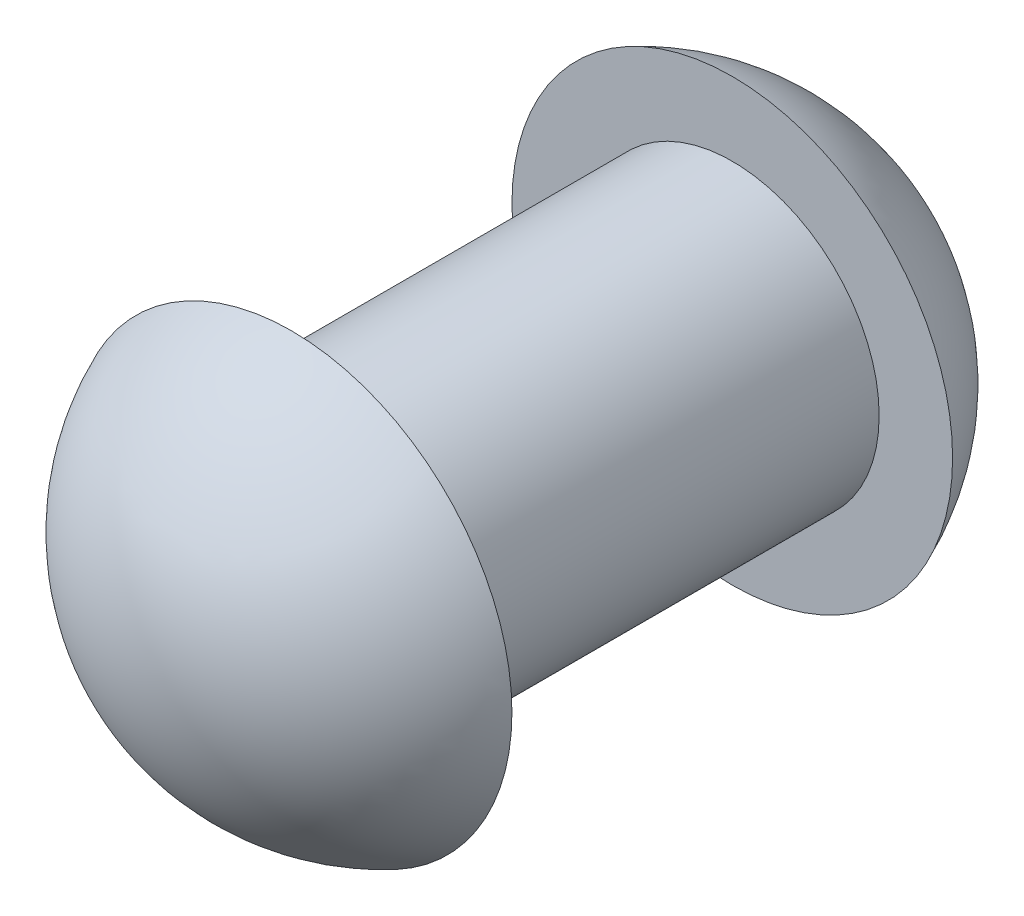
SolidWorks part; units mm, degrees
ref_plane "前视基准面" through (0, 0, 0) normal (0, 0, 1) x (1, 0, 0)
ref_plane "上视基准面" through (0, 0, 0) normal (0, 1, 0) x (1, 0, 0)
ref_plane "右视基准面" through (0, 0, 0) normal (1, 0, 0) x (0, 0, -1)
sketch "草图1" plane through (0, 0, 0) normal (0, 1, 0) x (1, 0, 0)
  line L0 (0, 2.5) -> (0, -2.5)
  line L1 (1.5, 1.5) -> (1, 1.5)
  line L2 (1, 1.5) -> (1, -1.5)
  line L3 (1, -1.5) -> (1.5, -1.5)
  arc A0 (0, 2.5) -> (1.5, 1.5) centre (0, 0.875) cw
  arc A1 (1.5, -1.5) -> (0, -2.5) centre (0, -0.875) cw
  point P3 (0, 0)
  point P10 (1, 0)
  point P11 (0.1939, -0.792)
  dimension "D1" = 0.5
  dimension "D2" = 1
  dimension "D3" = 3
  dimension "D4" = 5
revolve "旋转1" add sketch "草图1" angle 360 about L0
